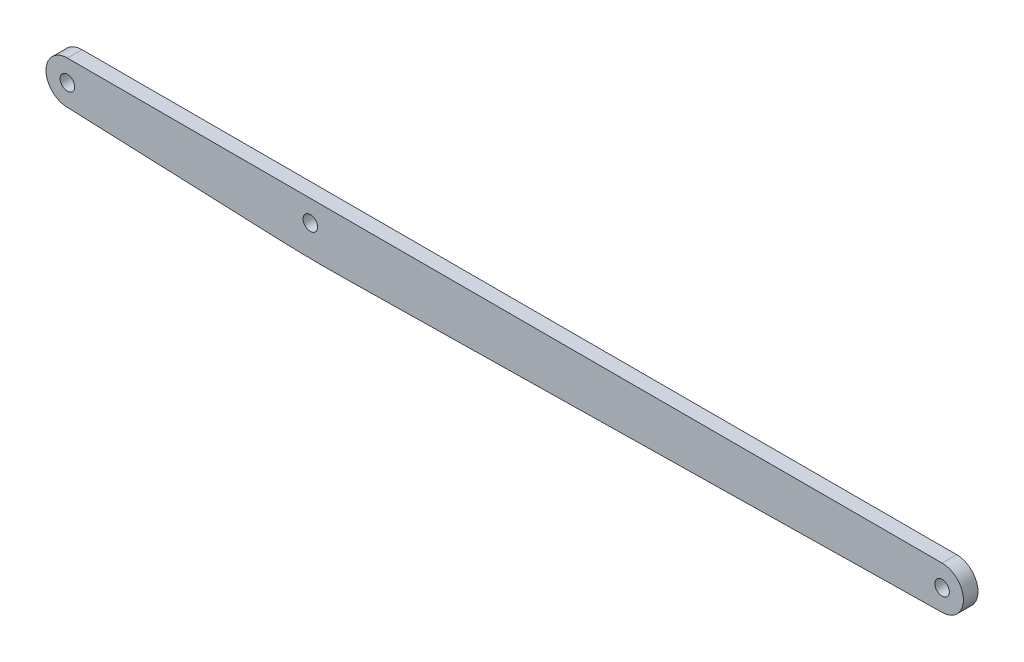
SolidWorks part; units mm, degrees
ref_plane "Front Plane" through (0, 0, 0) normal (0, 0, 1) x (1, 0, 0)
ref_plane "Top Plane" through (0, 0, 0) normal (0, 1, 0) x (1, 0, 0)
ref_plane "Right Plane" through (0, 0, 0) normal (1, 0, 0) x (0, 0, -1)
sketch "Sketch1" plane through (0, 0, 0) normal (0, 0, 1) x (1, 0, 0)
  line L0 (-180, 0) -> (180, 0) construction
  line L8 (-180, 8.792) -> (180, 8.792)
  line L10 (-180, -8.792) -> (-94.1159, -12.2977)
  line L11 (-65.874, -12.6522) -> (180, -8.792)
  arc A13 (-180, 8.792) -> (-180, -8.792) centre (-180, 0) ccw
  arc A14 (180, -8.792) -> (180, 8.792) centre (180, 0) ccw
  circle A15 centre (-180, 0) radius 3
  circle A16 centre (-80, 0) radius 3
  circle A17 centre (180, 0) radius 3
  arc A18 (-94.1159, -12.2977) -> (-65.874, -12.6522) centre (-73.723, 487.2862) ccw
  point P2 (0, 0)
  dimension "D2" = 100
  dimension "D3" = 6
  dimension "D5" = 6
  dimension "D4" = 6
  dimension "D1" = 360
  dimension "D6" = 500
extrude "Boss-Extrude1" add sketch "Sketch1" against normal blind 6
scale "Scale1" scale about centroid uniform scaling yes scale factor 0.5
